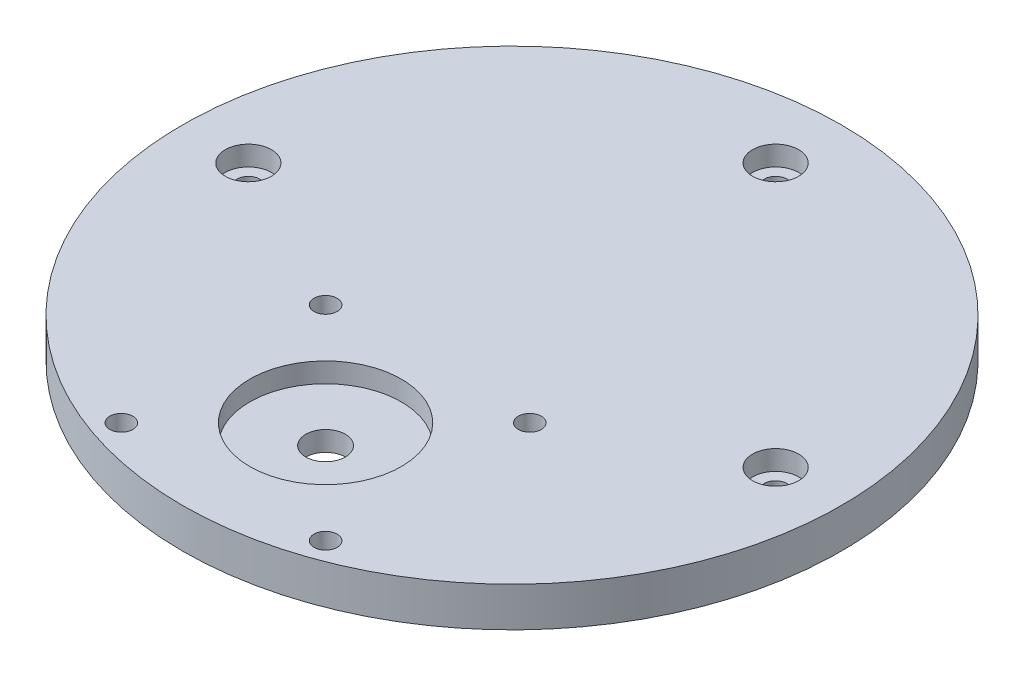
SolidWorks part; units mm, degrees
ref_plane "前视基准面" through (0, 0, 0) normal (0, 0, 1) x (1, 0, 0)
ref_plane "上视基准面" through (0, 0, 0) normal (0, 1, 0) x (1, 0, 0)
ref_plane "右视基准面" through (0, 0, 0) normal (1, 0, 0) x (0, 0, -1)
other "Configuration Table"
sketch "草图1" plane through (0, 0, 0) normal (0, 1, 0) x (1, 0, 0)
  circle A0 centre (0, 0) radius 50
  dimension "D1" = 100
extrude "凸台-拉伸1" add sketch "草图1" along normal blind 6
sketch "草图2" plane through (0, 6, 0) normal (0, 1, 0) x (1, 0, 0)
  circle A0 centre (0, 40) radius 1.75
  circle A1 centre (40, 0) radius 1.75
  circle A2 centre (-40, 0) radius 1.75
  dimension "D1" = 3.5
  dimension "D2" = 3.5
  dimension "D3" = 3.5
  dimension "D4" = 40
  dimension "D5" = 40
  dimension "D6" = 40
extrude "切除-拉伸1" cut sketch "草图2" against normal blind 24
sketch "草图4" plane through (0, 0, 0) normal (0, -1, 0) x (1, 0, 0)
  circle A0 centre (0, 28.2843) radius 3
  dimension "D1" = 6
extrude "切除-拉伸2" cut sketch "草图4" against normal blind 24
sketch "草图5" plane through (0, 6, 0) normal (0, 1, 0) x (1, 0, 0)
  circle A0 centre (0, -28.2843) radius 11.5
  dimension "D1" = 23
extrude "切除-拉伸3" cut sketch "草图5" against normal blind 3
sketch "草图6" plane through (0, 6, 0) normal (0, 1, 0) x (1, 0, 0)
  circle A0 centre (15.494, -12.7903) radius 1.75
  circle A1 centre (15.494, -43.7783) radius 1.75
  circle A2 centre (-15.494, -43.7783) radius 1.75
  circle A3 centre (-15.494, -12.7903) radius 1.75
  point P12 (0, -28.2843)
  dimension "D1" = 3.5
  dimension "D2" = 4
extrude "切除-拉伸4" cut sketch "草图6" against normal blind 37
sketch "草图7" plane through (0, 0, 0) normal (0, -1, 0) x (1, 0, 0)
  circle A0 centre (15.494, 43.7783) radius 3
  circle A1 centre (15.494, 12.7903) radius 3
  circle A2 centre (-15.494, 12.7903) radius 3
  circle A3 centre (-15.494, 43.7783) radius 3
  point P12 (0, 28.2843)
  dimension "D1" = 6
  dimension "D2" = 4
extrude "切除-拉伸5" cut sketch "草图7" against normal blind 3
sketch "草图8" plane through (0, 6, 0) normal (0, 1, 0) x (1, 0, 0)
  line L0 (-45, 40) -> (45, 40) construction
  circle A0 centre (0, 40) radius 3.5
  circle A1 centre (-40, 0) radius 3.5
  circle A2 centre (40, 0) radius 3.5
  dimension "D1" = 7
  dimension "D2" = 7
  dimension "D3" = 7
extrude "切除-拉伸6" cut sketch "草图8" against normal blind 3
